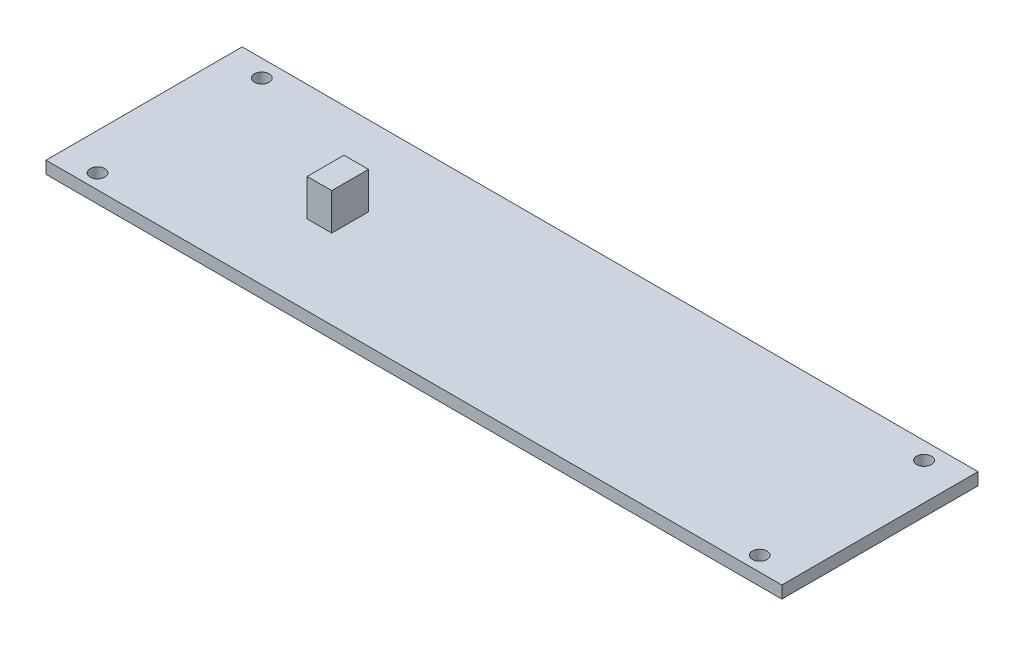
SolidWorks part; units mm, degrees
ref_plane "Front Plane" through (0, 0, 0) normal (0, 0, 1) x (1, 0, 0)
ref_plane "Top Plane" through (0, 0, 0) normal (0, 1, 0) x (1, 0, 0)
ref_plane "Right Plane" through (0, 0, 0) normal (1, 0, 0) x (0, 0, -1)
sketch "Sketch1" plane through (0, 0, 0) normal (0, 1, 0) x (1, 0, 0)
  line L1 (0, 0) -> (300, 0)
  line L2 (0, 0) -> (0, -80)
  line L3 (0, -80) -> (300, -80)
  line L4 (300, 0) -> (300, -80)
  dimension "D1" = 80
  dimension "D2" = 300
extrude "Boss-Extrude1" add sketch "Sketch1" along normal blind 5
sketch "Sketch2" plane through (0, 5, 0) normal (0, 1, 0) x (1, 0, 0)
  line L0 (300, 0) -> (0, 0) construction
  line L1 (0, 0) -> (0, -80) construction
  line L2 (150, 0) -> (150, -80) construction
  line L3 (0, -80) -> (300, -80) construction
  circle A0 centre (15, -7) radius 3
  circle A1 centre (15, -74) radius 3
  circle A2 centre (285, -7) radius 3
  circle A3 centre (285, -74) radius 3
  dimension "D1" = 6
  dimension "D2" = 6
  dimension "D5" = 67
  dimension "D6" = 7
  dimension "D7" = 15
  dimension "D8" = 15
extrude "Cut-Extrude2" cut sketch "Sketch2" against normal blind 5
sketch "Sketch4" plane through (0, 0, 0) normal (0, 1, 0) x (1, 0, 0)
  line L0 (0, 0) -> (0, -80) construction
  line L1 (84, -47.5) -> (74, -47.5)
  line L2 (84, -47.5) -> (84, -32.5)
  line L3 (84, -32.5) -> (74, -32.5)
  line L4 (74, -47.5) -> (74, -32.5)
  line L5 (300, 0) -> (0, 0) construction
  dimension "D1" = 15
  dimension "D2" = 10
  dimension "D3" = 74
  dimension "D4" = 32.5
extrude "Boss-Extrude2" add sketch "Sketch4" along normal blind 20
